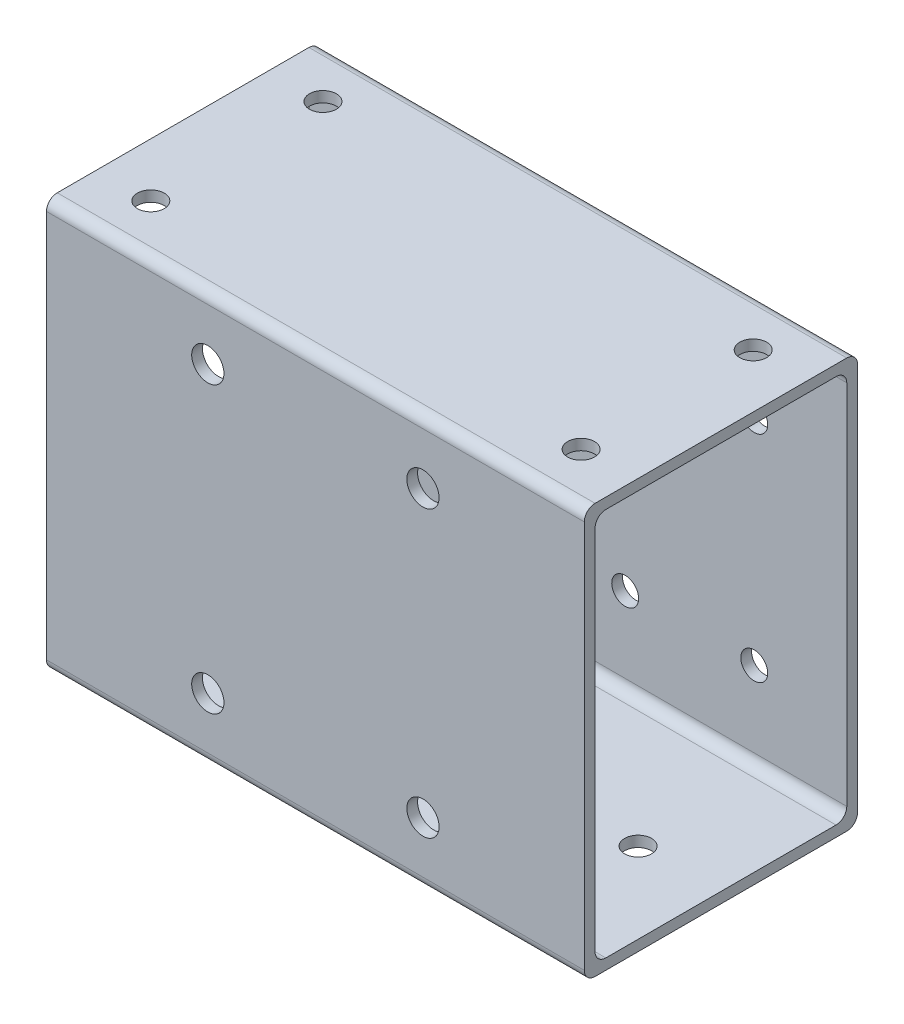
SolidWorks part; units mm, degrees
material "A500"
ref_plane "Alzado" through (0, 0, 0) normal (0, 0, 1) x (1, 0, 0)
ref_plane "Planta" through (0, 0, 0) normal (0, 1, 0) x (1, 0, 0)
ref_plane "Vista lateral" through (0, 0, 0) normal (1, 0, 0) x (0, 0, -1)
sketch "Sketch1" plane through (0, 0, 0) normal (1, 0, 0) x (0, 0, -1)
  line L1 (25.4, 38.1) -> (-25.4, 38.1)
  line L2 (25.4, 38.1) -> (25.4, -38.1)
  line L3 (25.4, -38.1) -> (-25.4, -38.1)
  line L4 (-25.4, 38.1) -> (-25.4, -38.1)
  line L5 (25.4, 38.1) -> (-25.4, -38.1) construction
  line L6 (25.4, -38.1) -> (-25.4, 38.1) construction
  point P0 (0, 0)
  dimension "D1" = 76.2
  dimension "D2" = 50.8
extrude "Boss-Extrude1" add sketch "Sketch1" against normal blind 100
sketch "Sketch2" plane through (0, 0, 0) normal (1, 0, 0) x (0, 0, -1)
  line L0 (25.4, 38.1) -> (-25.4, 38.1) construction
  line L1 (23.4, 36.1) -> (-23.4, 36.1)
  line L2 (23.4, 36.1) -> (23.4, -36.1)
  line L3 (23.4, -36.1) -> (-23.4, -36.1)
  line L4 (-23.4, 36.1) -> (-23.4, -36.1)
  line L5 (23.4, 36.1) -> (-23.4, -36.1) construction
  line L6 (23.4, -36.1) -> (-23.4, 36.1) construction
  line L7 (25.4, -38.1) -> (25.4, 38.1) construction
  point P0 (0, 0)
  dimension "D1" = 2
  dimension "D2" = 2
extrude "Cut-Extrude1" cut sketch "Sketch2" against normal through all
fillet "Fillet2" radius 2 8 edges at (-50, -38.1, -25.4) (-50, -38.1, 25.4) (-50, 38.1, 25.4) (-50, 38.1, -25.4) (-50, -36.1, -23.4) (-50, 36.1, -23.4) (-50, -36.1, 23.4) (-50, 36.1, 23.4)
sketch "Croquis2" plane through (0, 0, 25.4) normal (0, 0, 1) x (1, 0, 0)
  line L0 (-50, 36.1) -> (-50, -36.1) construction
  line L1 (0, 36.1) -> (-100, 36.1) construction
  line L2 (-100, -36.1) -> (0, -36.1) construction
  line L4 (-30, 26.5) -> (-70, 26.5)
  line L5 (-30, 26.5) -> (-30, -26.5)
  line L6 (-30, -26.5) -> (-70, -26.5)
  line L7 (-70, 26.5) -> (-70, -26.5)
  line L8 (-30, 26.5) -> (-70, -26.5) construction
  line L9 (-30, -26.5) -> (-70, 26.5) construction
  circle A0 centre (-70, 26.5) radius 3
  circle A1 centre (-30, 26.5) radius 3
  circle A2 centre (-30, -26.5) radius 3
  circle A3 centre (-70, -26.5) radius 3
  point P6 (-50, 0)
  dimension "D3" = 6
  dimension "D4" = 6
  dimension "D5" = 6
  dimension "D6" = 6
  dimension "D1" = 53
  dimension "D2" = 40
extrude "Cortar-Extruir2" cut sketch "Croquis2" against normal blind 10 contours L5 A1 L4 | L4 A1 L5 | L4 A0 L7 | L7 A0 L4 | L6 A3 L7 | L7 A3 L6 | L6 A2 L5 | L5 A2 L6
sketch "Croquis4" plane through (0, 0, -25.4) normal (0, 0, -1) x (-1, 0, 0)
  line L0 (49.2, 38.1) -> (49.2, -38.1) construction
  line L2 (0, 38.1) -> (100, 38.1) construction
  line L3 (100, -38.1) -> (0, -38.1) construction
  line L6 (100, -36.1) -> (100, 36.1) construction
  line L7 (100, 23.1) -> (49.2, 23.1) construction
  line L8 (100, -23.1) -> (49.2, -23.1) construction
  line L9 (49.2, 0) -> (100, 0) construction
  circle A1 centre (90, 23.1) radius 2.5
  circle A2 centre (59.2, 23.1) radius 2.5
  circle A3 centre (59.2, -23.1) radius 2.5
  circle A4 centre (90, -23.1) radius 2.5
  circle A5 centre (74.6, 0) radius 2.5
  dimension "D3" = 15
  dimension "D4" = 5
  dimension "D5" = 5
  dimension "D6" = 5
  dimension "D7" = 5
  dimension "D8" = 5
  dimension "D1" = 50.8
  dimension "D2" = 15
  dimension "D9" = 10
  dimension "D10" = 10
  dimension "D11" = 10
  dimension "D12" = 10
extrude "Cortar-Extruir5" [suppressed] cut sketch "Croquis4" against normal blind 10
sketch "Croquis6" plane through (0, 0, -25.4) normal (0, 0, -1) x (-1, 0, 0)
  line L0 (49.2, 38.1) -> (49.2, -38.1) construction
  line L8 (0, 0) -> (41.2, 0) construction
  line L9 (41.2, 20) -> (17.2, 20)
  line L10 (41.2, 20) -> (41.2, -20)
  line L11 (41.2, -20) -> (17.2, -20)
  line L12 (17.2, 20) -> (17.2, -20)
  line L13 (0, -36.1) -> (0, 36.1) construction
  line L14 (0, 38.1) -> (100, 38.1) construction
  line L15 (100, -38.1) -> (0, -38.1) construction
  line L16 (100, -36.1) -> (100, 36.1) construction
  circle A0 centre (17.2, 20) radius 2.5
  circle A1 centre (17.2, -20) radius 2.5
  circle A2 centre (41.2, -20) radius 2.5
  circle A3 centre (41.2, 20) radius 2.5
  dimension "D5" = 5
  dimension "D6" = 5
  dimension "D7" = 5
  dimension "D8" = 5
  dimension "D1" = 8
  dimension "D2" = 24
  dimension "D3" = 40
  dimension "D4" = 20
  dimension "D9" = 50.8
extrude "Cortar-Extruir6" cut sketch "Croquis6" against normal blind 10 contours A0 | A3 | A2 | A1
sketch "Croquis7" plane through (0, -38.1, 0) normal (0, -1, 0) x (1, 0, 0)
  line L0 (0, 0.4) -> (-100, 0.4) construction
  line L1 (0, 23.4) -> (0, -23.4) construction
  line L2 (-100, 23.4) -> (-100, -23.4) construction
  line L3 (-100, 25.4) -> (0, 25.4) construction
  circle A0 centre (-15, 0.4) radius 2.5
  circle A1 centre (-80, 0.4) radius 2.5
  dimension "D2" = 5
  dimension "D5" = 5
  dimension "D1" = 25
  dimension "D3" = 15
  dimension "D4" = 20
extrude "Cortar-Extruir7" cut sketch "Croquis7" against normal blind 10
sketch "Croquis8" plane through (0, 38.1, 0) normal (0, 1, 0) x (1, 0, 0)
  line L0 (-100, 0) -> (0, 0) construction
  line L1 (-100, 23.4) -> (-100, -23.4) construction
  line L3 (-10, 16) -> (-90, 16)
  line L4 (-10, 16) -> (-10, -16)
  line L5 (-10, -16) -> (-90, -16)
  line L6 (-90, 16) -> (-90, -16)
  line L7 (-10, 16) -> (-90, -16) construction
  line L8 (-10, -16) -> (-90, 16) construction
  circle A0 centre (-90, 16) radius 2.5
  circle A1 centre (-10, 16) radius 2.5
  circle A2 centre (-90, -16) radius 2.5
  circle A3 centre (-10, -16) radius 2.5
  point P5 (-50, 0)
  dimension "D3" = 5
  dimension "D4" = 5
  dimension "D5" = 5
  dimension "D6" = 5
  dimension "D1" = 80
  dimension "D2" = 32
extrude "Cortar-Extruir8" cut sketch "Croquis8" against normal blind 10 contours A0 | A2 | A1 | A3
